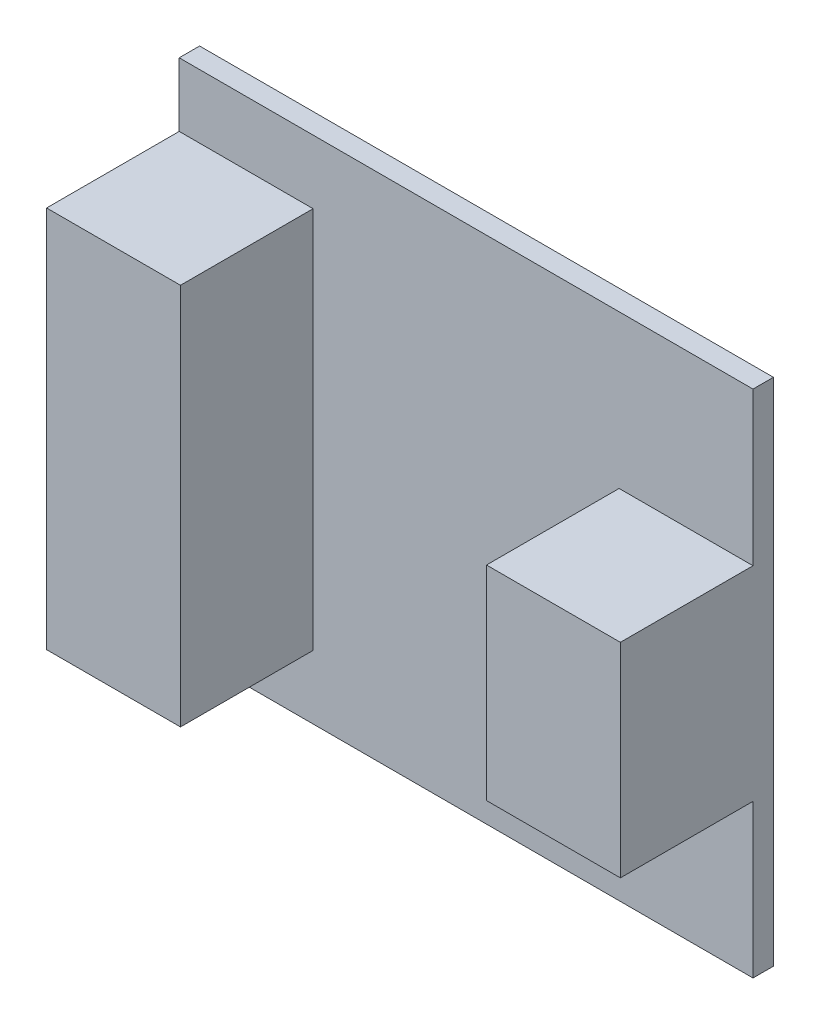
SolidWorks part; units mm, degrees
ref_plane "Front Plane" through (0, 0, 0) normal (0, 0, 1) x (1, 0, 0)
ref_plane "Top Plane" through (0, 0, 0) normal (0, 1, 0) x (1, 0, 0)
ref_plane "Right Plane" through (0, 0, 0) normal (1, 0, 0) x (0, 0, -1)
sketch "Sketch1" plane through (0, 0, 0) normal (0, 0, 1) x (1, 0, 0)
  line L0 (-22.5, -20) -> (22.5, -20)
  line L1 (22.5, -20) -> (22.5, 20)
  line L2 (22.5, 20) -> (-22.5, 20)
  line L3 (-22.5, 20) -> (-22.5, -20)
extrude "PCB" add sketch "Sketch1" along normal blind 1.6
ref_plane "P_Front_1p6" through (0, 0, 1.6) normal (0, 0, 1) x (1, 0, 0)
sketch "Sketch2" plane through (0, 0, 1.6) normal (0, 0, 1) x (1, 0, 0)
  line L0 (-22.5, -15) -> (-12, -15)
  line L1 (-12, -15) -> (-12, 15)
  line L2 (-12, 15) -> (-22.5, 15)
  line L3 (-22.5, 15) -> (-22.5, -15)
extrude "Motor_terminals" add sketch "Sketch2" along normal blind 10.4
sketch "Sketch3" plane through (0, 0, 1.6) normal (0, 0, 1) x (1, 0, 0)
  line L0 (12, -8) -> (22.5, -8)
  line L1 (22.5, -8) -> (22.5, 8)
  line L2 (22.5, 8) -> (12, 8)
  line L3 (12, 8) -> (12, -8)
extrude "Power_terminal" add sketch "Sketch3" along normal blind 10.4
